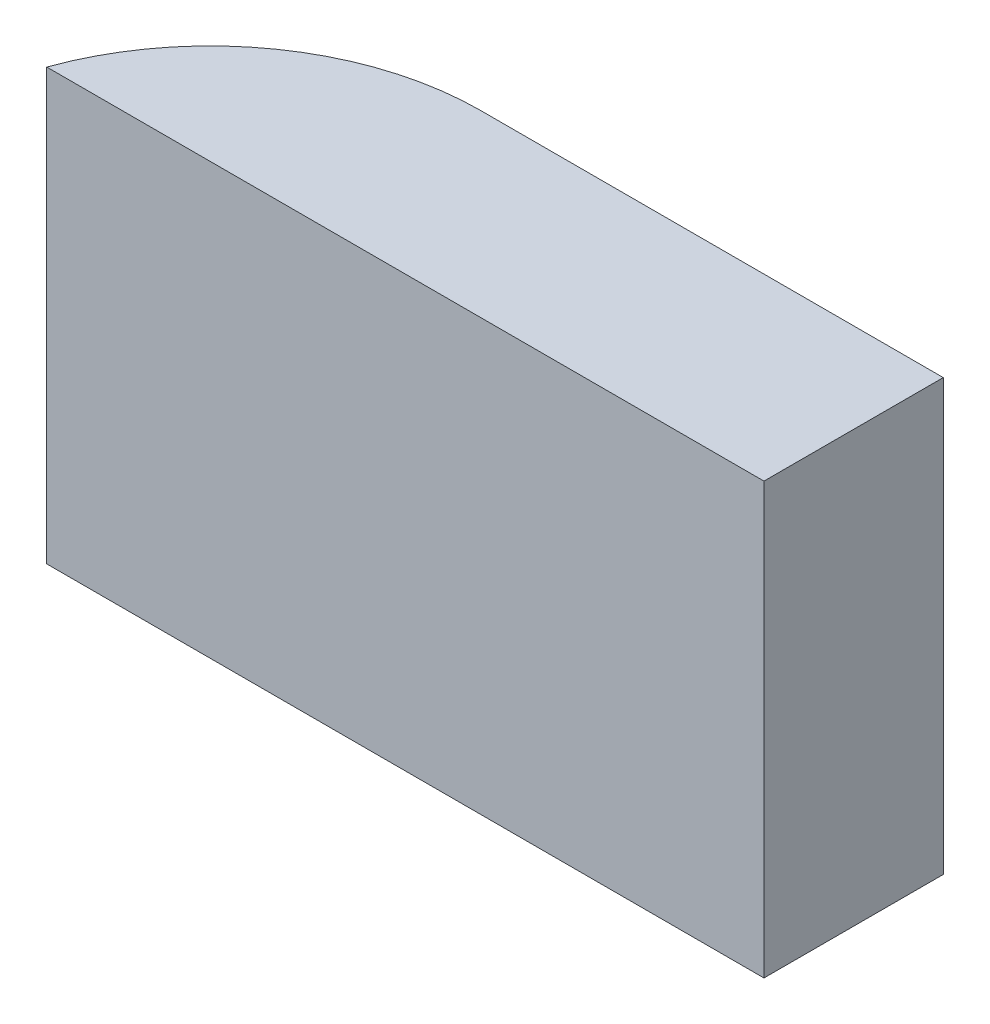
SolidWorks part; units mm, degrees
ref_plane "Front Plane" through (0, 0, 0) normal (0, 0, 1) x (1, 0, 0)
ref_plane "Top Plane" through (0, 0, 0) normal (0, 1, 0) x (1, 0, 0)
ref_plane "Right Plane" through (0, 0, 0) normal (1, 0, 0) x (0, 0, -1)
sketch "Sketch1" plane through (0, 0, 0) normal (0, 1, 0) x (1, 0, 0)
  line L0 (0, 0) -> (0, -31.75)
  line L1 (0, -31.75) -> (-127, -31.75)
  line L2 (0, 0) -> (-81.8678, 0)
  arc A0 (-81.8678, 0) -> (-127, -31.75) centre (-81.8678, -47.9525) ccw
  point P6 (-81.8678, 0)
  dimension "D1" = 31.75
  dimension "D2" = 127
extrude "Boss-Extrude1" add sketch "Sketch1" along normal blind 76.2
